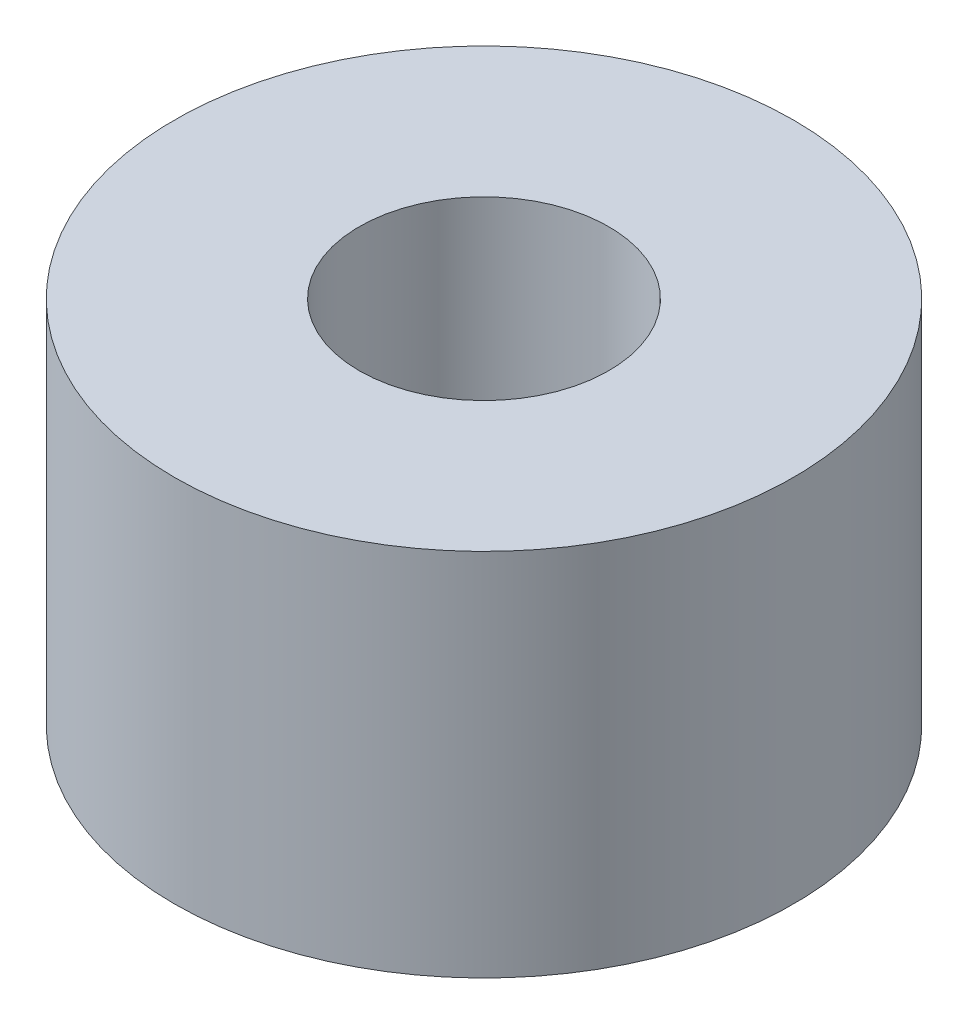
SolidWorks part; units mm, degrees
ref_plane "Front Plane" through (0, 0, 0) normal (0, 0, 1) x (1, 0, 0)
ref_plane "Top Plane" through (0, 0, 0) normal (0, 1, 0) x (1, 0, 0)
ref_plane "Right Plane" through (0, 0, 0) normal (1, 0, 0) x (0, 0, -1)
sketch "Sketch2" plane through (0, 0, 0) normal (0, 1, 0) x (1, 0, 0)
  circle A0 centre (0, 0) radius 3.3782
  circle A1 centre (0, 0) radius 8.3782
  dimension "D1" = 6.7564
  dimension "D2" = 5
extrude "Boss-Extrude1" add sketch "Sketch2" along normal blind 10
